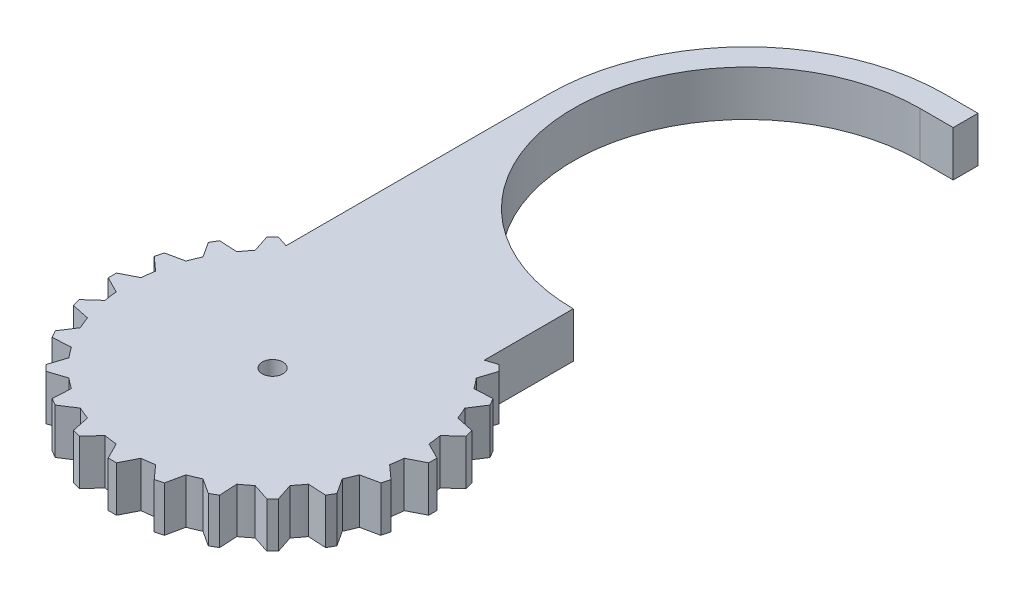
SolidWorks part; units mm, degrees
ref_plane "Front Plane" through (0, 0, 0) normal (0, 0, 1) x (1, 0, 0)
ref_plane "Top Plane" through (0, 0, 0) normal (0, 1, 0) x (1, 0, 0)
ref_plane "Right Plane" through (0, 0, 0) normal (1, 0, 0) x (0, 0, -1)
sketch "Sketch1" plane through (0, 0, 0) normal (0, 1, 0) x (1, 0, 0)
  line L0 (0, 21) -> (0, 24)
  line L1 (0, -21) -> (0, -31.7724)
  line L2 (-24, 0) -> (-24, -31.7724)
  line L14 (2.0714, -32.0357) -> (1.3895, -34.1318)
  line L15 (1.3643, -31.3286) -> (0, -31.7724)
  line L16 (1.3643, -31.3286) -> (2.0714, -32.0357)
  line L17 (5.0509, -36.133) -> (3.8497, -37.9812)
  line L18 (4.5509, -35.267) -> (2.3497, -35.3832)
  line L19 (4.5509, -35.267) -> (5.0509, -36.133)
  line L20 (6.8684, -40.8619) -> (5.2297, -42.3362)
  line L21 (6.6096, -39.8959) -> (4.4533, -39.4384)
  line L22 (6.6096, -39.8959) -> (6.8684, -40.8619)
  line L23 (7.4, -45.9) -> (5.4356, -46.9)
  line L24 (7.4, -44.9) -> (5.4356, -43.9)
  line L25 (7.4, -44.9) -> (7.4, -45.9)
  line L26 (6.6096, -50.9041) -> (4.4533, -51.3616)
  line L27 (6.8684, -49.9381) -> (5.2297, -48.4638)
  line L28 (6.8684, -49.9381) -> (6.6096, -50.9041)
  line L29 (4.5509, -55.533) -> (2.3497, -55.4168)
  line L30 (5.0509, -54.667) -> (3.8497, -52.8188)
  line L31 (5.0509, -54.667) -> (4.5509, -55.533)
  line L32 (1.3643, -59.4714) -> (-0.7318, -58.7895)
  line L33 (2.0714, -58.7643) -> (1.3895, -56.6682)
  line L34 (2.0714, -58.7643) -> (1.3643, -59.4714)
  line L35 (-2.733, -62.4509) -> (-4.5812, -61.2497)
  line L36 (-1.867, -61.9509) -> (-1.9832, -59.7497)
  line L37 (-1.867, -61.9509) -> (-2.733, -62.4509)
  line L38 (-7.4619, -64.2684) -> (-8.9362, -62.6297)
  line L39 (-6.4959, -64.0096) -> (-6.0384, -61.8533)
  line L40 (-6.4959, -64.0096) -> (-7.4619, -64.2684)
  line L41 (-12.5, -64.8) -> (-13.5, -62.8356)
  line L42 (-11.5, -64.8) -> (-10.5, -62.8356)
  line L43 (-11.5, -64.8) -> (-12.5, -64.8)
  line L44 (-17.5041, -64.0096) -> (-17.9616, -61.8533)
  line L45 (-16.5381, -64.2684) -> (-15.0638, -62.6297)
  line L46 (-16.5381, -64.2684) -> (-17.5041, -64.0096)
  line L47 (-22.133, -61.9509) -> (-22.0168, -59.7497)
  line L48 (-21.267, -62.4509) -> (-19.4188, -61.2497)
  line L49 (-21.267, -62.4509) -> (-22.133, -61.9509)
  line L50 (-26.0714, -58.7643) -> (-25.3895, -56.6682)
  line L51 (-25.3643, -59.4714) -> (-23.2682, -58.7895)
  line L52 (-25.3643, -59.4714) -> (-26.0714, -58.7643)
  line L53 (-29.0509, -54.667) -> (-27.8497, -52.8188)
  line L54 (-28.5509, -55.533) -> (-26.3497, -55.4168)
  line L55 (-28.5509, -55.533) -> (-29.0509, -54.667)
  line L56 (-30.8684, -49.9381) -> (-29.2297, -48.4638)
  line L57 (-30.6096, -50.9041) -> (-28.4533, -51.3616)
  line L58 (-30.6096, -50.9041) -> (-30.8684, -49.9381)
  line L59 (-31.4, -44.9) -> (-29.4356, -43.9)
  line L60 (-31.4, -45.9) -> (-29.4356, -46.9)
  line L61 (-31.4, -45.9) -> (-31.4, -44.9)
  line L62 (-30.6096, -39.8959) -> (-28.4533, -39.4384)
  line L63 (-30.8684, -40.8619) -> (-29.2297, -42.3362)
  line L64 (-30.8684, -40.8619) -> (-30.6096, -39.8959)
  line L65 (-28.5509, -35.267) -> (-26.3497, -35.3832)
  line L66 (-29.0509, -36.133) -> (-27.8497, -37.9812)
  line L67 (-29.0509, -36.133) -> (-28.5509, -35.267)
  line L68 (-25.3643, -31.3286) -> (-24, -31.7724)
  line L69 (-26.0714, -32.0357) -> (-25.3895, -34.1318)
  line L70 (-26.0714, -32.0357) -> (-25.3643, -31.3286)
  arc A0 (0, 21) -> (0, -21) centre (0, 0) ccw
  arc A1 (0, 24) -> (-24, 0) centre (0, 0) ccw
  arc A3 (-25.3895, -34.1318) -> (-26.3497, -35.3832) centre (-12, -45.4) ccw
  arc A4 (-27.8497, -37.9812) -> (-28.4533, -39.4384) centre (-12, -45.4) ccw
  arc A5 (-29.2297, -42.3362) -> (-29.4356, -43.9) centre (-12, -45.4) ccw
  arc A6 (-29.4356, -46.9) -> (-29.2297, -48.4638) centre (-12, -45.4) ccw
  arc A7 (-28.4533, -51.3616) -> (-27.8497, -52.8188) centre (-12, -45.4) ccw
  arc A8 (-26.3497, -55.4168) -> (-25.3895, -56.6682) centre (-12, -45.4) ccw
  arc A9 (-23.2682, -58.7895) -> (-22.0168, -59.7497) centre (-12, -45.4) ccw
  arc A10 (-19.4188, -61.2497) -> (-17.9616, -61.8533) centre (-12, -45.4) ccw
  arc A11 (-15.0638, -62.6297) -> (-13.5, -62.8356) centre (-12, -45.4) ccw
  arc A12 (-10.5, -62.8356) -> (-8.9362, -62.6297) centre (-12, -45.4) ccw
  arc A13 (-6.0384, -61.8533) -> (-4.5812, -61.2497) centre (-12, -45.4) ccw
  arc A14 (-1.9832, -59.7497) -> (-0.7318, -58.7895) centre (-12, -45.4) ccw
  arc A15 (1.3895, -56.6682) -> (2.3497, -55.4168) centre (-12, -45.4) ccw
  arc A16 (3.8497, -52.8188) -> (4.4533, -51.3616) centre (-12, -45.4) ccw
  arc A17 (5.2297, -48.4638) -> (5.4356, -46.9) centre (-12, -45.4) ccw
  arc A18 (5.4356, -43.9) -> (5.2297, -42.3362) centre (-12, -45.4) ccw
  arc A19 (4.4533, -39.4384) -> (3.8497, -37.9812) centre (-12, -45.4) ccw
  arc A20 (2.3497, -35.3832) -> (1.3895, -34.1318) centre (-12, -45.4) ccw
  point P110 (-12, -45.4)
  dimension "D1" = 42
  dimension "D6" = 35
  dimension "D2" = 3
  dimension "D3" = 24
extrude "Boss-Extrude1" add sketch "Sketch1" along normal blind 3
sketch "Sketch3" plane through (0, 0, 0) normal (1, 0, 0) x (0, 0, -1)
  line L4 (21, 0) -> (24, 0)
  line L5 (24, 0) -> (24, 3)
  line L6 (24, 3) -> (21, 3)
  line L7 (21, 3) -> (21, 0)
  line L8 (21, 0) -> (24, 0)
  line L9 (24, 0) -> (24, 3)
  line L10 (24, 3) -> (21, 3)
  line L11 (21, 3) -> (21, 0)
  dimension "D1" = 0
extrude "Boss-Extrude2" add sketch "Sketch3" along normal blind 4
sketch "Sketch4" plane through (0, 0, 0) normal (0, -1, 0) x (1, 0, 0)
  line L65 (0, 31.7724) -> (0, 21)
  line L66 (1.3643, 31.3286) -> (0, 31.7724)
  line L67 (2.0714, 32.0357) -> (1.3643, 31.3286)
  line L68 (1.3895, 34.1318) -> (2.0714, 32.0357)
  line L69 (4.5509, 35.267) -> (2.3497, 35.3832)
  line L70 (5.0509, 36.133) -> (4.5509, 35.267)
  line L71 (3.8497, 37.9812) -> (5.0509, 36.133)
  line L72 (6.6096, 39.8959) -> (4.4533, 39.4384)
  line L73 (6.8684, 40.8619) -> (6.6096, 39.8959)
  line L74 (5.2297, 42.3362) -> (6.8684, 40.8619)
  line L75 (7.4, 44.9) -> (5.4356, 43.9)
  line L76 (7.4, 45.9) -> (7.4, 44.9)
  line L77 (5.4356, 46.9) -> (7.4, 45.9)
  line L78 (6.8684, 49.9381) -> (5.2297, 48.4638)
  line L79 (6.6096, 50.9041) -> (6.8684, 49.9381)
  line L80 (4.4533, 51.3616) -> (6.6096, 50.9041)
  line L81 (5.0509, 54.667) -> (3.8497, 52.8188)
  line L82 (4.5509, 55.533) -> (5.0509, 54.667)
  line L83 (2.3497, 55.4168) -> (4.5509, 55.533)
  line L84 (2.0714, 58.7643) -> (1.3895, 56.6682)
  line L85 (1.3643, 59.4714) -> (2.0714, 58.7643)
  line L86 (-0.7318, 58.7895) -> (1.3643, 59.4714)
  line L87 (-1.867, 61.9509) -> (-1.9832, 59.7497)
  line L88 (-2.733, 62.4509) -> (-1.867, 61.9509)
  line L89 (-4.5812, 61.2497) -> (-2.733, 62.4509)
  line L90 (-6.4959, 64.0096) -> (-6.0384, 61.8533)
  line L91 (-7.4619, 64.2684) -> (-6.4959, 64.0096)
  line L92 (-8.9362, 62.6297) -> (-7.4619, 64.2684)
  line L93 (-11.5, 64.8) -> (-10.5, 62.8356)
  line L94 (-12.5, 64.8) -> (-11.5, 64.8)
  line L95 (-13.5, 62.8356) -> (-12.5, 64.8)
  line L96 (-16.5381, 64.2684) -> (-15.0638, 62.6297)
  line L97 (-17.5041, 64.0096) -> (-16.5381, 64.2684)
  line L98 (-17.9616, 61.8533) -> (-17.5041, 64.0096)
  line L99 (-21.267, 62.4509) -> (-19.4188, 61.2497)
  line L100 (-22.133, 61.9509) -> (-21.267, 62.4509)
  line L101 (-22.0168, 59.7497) -> (-22.133, 61.9509)
  line L102 (-25.3643, 59.4714) -> (-23.2682, 58.7895)
  line L103 (-26.0714, 58.7643) -> (-25.3643, 59.4714)
  line L104 (-25.3895, 56.6682) -> (-26.0714, 58.7643)
  line L105 (-28.5509, 55.533) -> (-26.3497, 55.4168)
  line L106 (-29.0509, 54.667) -> (-28.5509, 55.533)
  line L107 (-27.8497, 52.8188) -> (-29.0509, 54.667)
  line L108 (-30.6096, 50.9041) -> (-28.4533, 51.3616)
  line L109 (-30.8684, 49.9381) -> (-30.6096, 50.9041)
  line L110 (-29.2297, 48.4638) -> (-30.8684, 49.9381)
  line L111 (-31.4, 45.9) -> (-29.4356, 46.9)
  line L112 (-31.4, 44.9) -> (-31.4, 45.9)
  line L113 (-29.4356, 43.9) -> (-31.4, 44.9)
  line L114 (-30.8684, 40.8619) -> (-29.2297, 42.3362)
  line L115 (-30.6096, 39.8959) -> (-30.8684, 40.8619)
  line L116 (-28.4533, 39.4384) -> (-30.6096, 39.8959)
  line L117 (-29.0509, 36.133) -> (-27.8497, 37.9812)
  line L118 (-28.5509, 35.267) -> (-29.0509, 36.133)
  line L119 (-26.3497, 35.3832) -> (-28.5509, 35.267)
  line L120 (-26.0714, 32.0357) -> (-25.3895, 34.1318)
  line L121 (-25.3643, 31.3286) -> (-26.0714, 32.0357)
  line L122 (-24, 31.7724) -> (-25.3643, 31.3286)
  line L123 (-24, 0) -> (-24, 31.7724)
  line L124 (4, -24) -> (0, -24)
  line L125 (4, -21) -> (4, -24)
  line L126 (0, -21) -> (4, -21)
  line L127 (-9.015, 25.1) -> (-7.0251, 44.9)
  line L128 (-16.9749, 44.9) -> (-14.985, 25.1)
  arc A22 (2.3497, 35.3832) -> (1.3895, 34.1318) centre (-12, 45.4) cw
  arc A23 (4.4533, 39.4384) -> (3.8497, 37.9812) centre (-12, 45.4) cw
  arc A24 (5.4356, 43.9) -> (5.2297, 42.3362) centre (-12, 45.4) cw
  arc A25 (5.2297, 48.4638) -> (5.4356, 46.9) centre (-12, 45.4) cw
  arc A26 (3.8497, 52.8188) -> (4.4533, 51.3616) centre (-12, 45.4) cw
  arc A27 (1.3895, 56.6682) -> (2.3497, 55.4168) centre (-12, 45.4) cw
  arc A28 (-1.9832, 59.7497) -> (-0.7318, 58.7895) centre (-12, 45.4) cw
  arc A29 (-6.0384, 61.8533) -> (-4.5812, 61.2497) centre (-12, 45.4) cw
  arc A30 (-10.5, 62.8356) -> (-8.9362, 62.6297) centre (-12, 45.4) cw
  arc A31 (-15.0638, 62.6297) -> (-13.5, 62.8356) centre (-12, 45.4) cw
  arc A32 (-19.4188, 61.2497) -> (-17.9616, 61.8533) centre (-12, 45.4) cw
  arc A33 (-23.2682, 58.7895) -> (-22.0168, 59.7497) centre (-12, 45.4) cw
  arc A34 (-26.3497, 55.4168) -> (-25.3895, 56.6682) centre (-12, 45.4) cw
  arc A35 (-28.4533, 51.3616) -> (-27.8497, 52.8188) centre (-12, 45.4) cw
  arc A36 (-29.4356, 46.9) -> (-29.2297, 48.4638) centre (-12, 45.4) cw
  arc A37 (-29.2297, 42.3362) -> (-29.4356, 43.9) centre (-12, 45.4) cw
  arc A38 (-27.8497, 37.9812) -> (-28.4533, 39.4384) centre (-12, 45.4) cw
  arc A39 (-25.3895, 34.1318) -> (-26.3497, 35.3832) centre (-12, 45.4) cw
  arc A40 (0, -24) -> (-24, 0) centre (0, 0) cw
  arc A41 (0, -21) -> (0, 21) centre (0, 0) cw
  arc A42 (-9.015, 25.1) -> (-14.985, 25.1) centre (-12, 25.4) cw
  arc A43 (-16.9749, 44.9) -> (-7.0251, 44.9) centre (-12, 45.4) cw
extrude "Boss-Extrude3" add sketch "Sketch4" along normal blind 2.5
sketch "Sketch5" plane through (0, 0, 0) normal (0, -1, 0) x (1, 0, 0)
  circle A0 centre (-12, 45.4) radius 1.25
extrude "Cut-Extrude1" cut sketch "Sketch5" against normal blind 16.5
